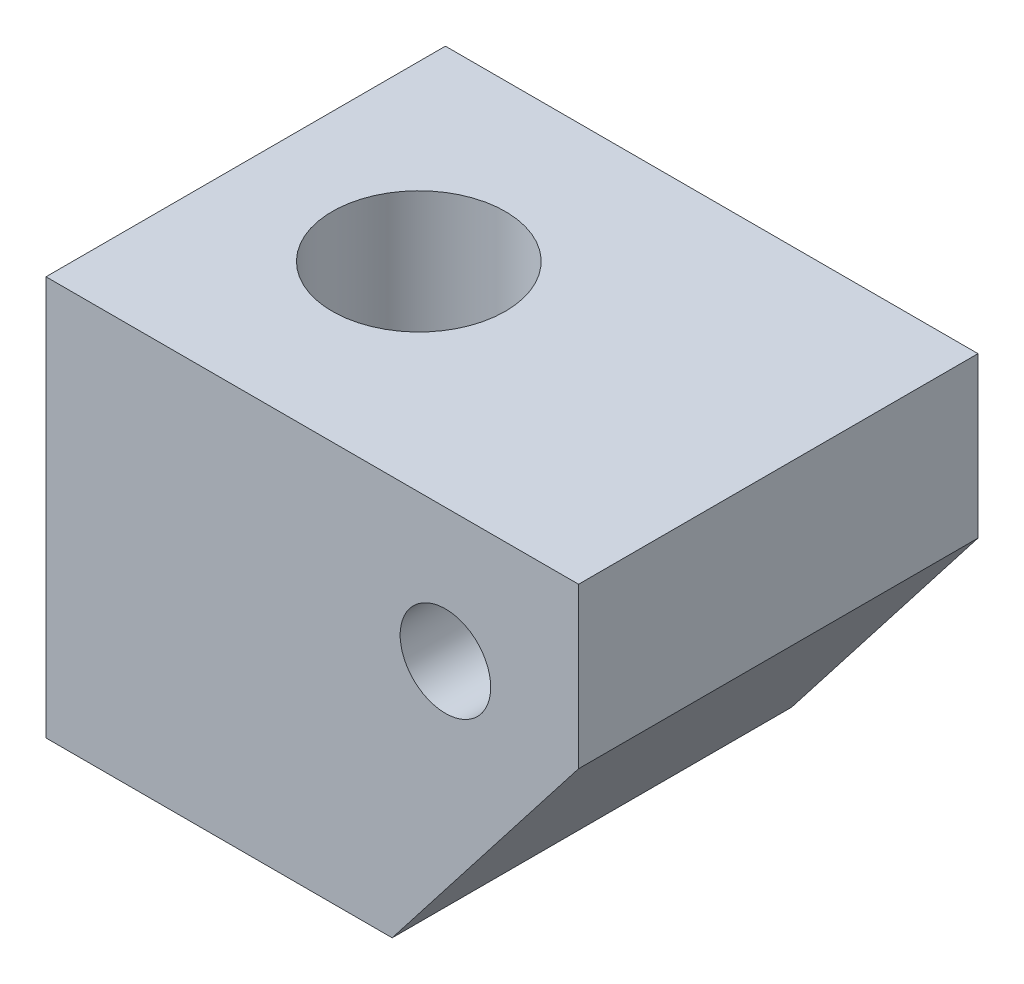
SolidWorks part; units mm, degrees
ref_plane "Piano frontale" through (0, 0, 0) normal (0, 0, 1) x (1, 0, 0)
ref_plane "Piano superiore" through (0, 0, 0) normal (0, 1, 0) x (1, 0, 0)
ref_plane "Piano destro" through (0, 0, 0) normal (1, 0, 0) x (0, 0, -1)
sketch "Schizzo1" plane through (0, 0, 0) normal (0, 0, 1) x (1, 0, 0)
  line L0 (0, 0) -> (-13, 0)
  line L1 (-13, 0) -> (-13, 15)
  line L2 (-13, 15) -> (7, 15)
  line L3 (7, 15) -> (7, 9)
  line L4 (7, 9) -> (0, 0)
  dimension "D1" = 20
  dimension "D2" = 15
  dimension "D3" = 13
  dimension "D4" = 6
extrude "Estrusione-Estrusione1" add sketch "Schizzo1" along normal blind 15
hole_wizard "Foro per Vite M3-1" positions "Schizzo3" profile "Schizzo4" hole size "M3" standard "ISO" end condition through all
sketch "Schizzo3" plane through (0, 0, 15) normal (0, 0, 1) x (1, 0, 0)
  line L0 (7, 9) -> (7, 15) construction
  line L2 (7, 15) -> (-13, 15) construction
  point P0 (2, 10)
  point P9 (1.0575, 15)
  dimension "D1" = 5
  dimension "D2" = 5
sketch "Schizzo4" plane through (2, 10, 15) normal (1, 0, 0) x (0, -1, 0)
  line L0 (0, 0) -> (0, 15)
  line L1 (0, 15) -> (1.7, 15)
  line L2 (1.7, 15) -> (1.7, 0)
  line L5 (1.7, 0) -> (0, 0)
  line L11 (0, -6.35) -> (0, 107.95) construction
  dimension "Thru Hole Dia." = 3.4
  dimension "Thru Hole Depth" = 15
sketch "Schizzo5" plane through (0, 0, 0) normal (0, -1, 0) x (-1, 0, 0)
  line L0 (6.5, -15) -> (6.5, 2.1848) construction
  line L1 (13, -15) -> (0, -15) construction
  line L2 (16.0553, -7.5) -> (0, -7.5) construction
  line L3 (0, -15) -> (0, 0) construction
  line L4 (13, 0) -> (0, 0) construction
  circle A0 centre (6.5, -7.5) radius 3.25
  dimension "D1" = 6.5
extrude "Taglio-Estrusione1" cut sketch "Schizzo5" against normal through all
